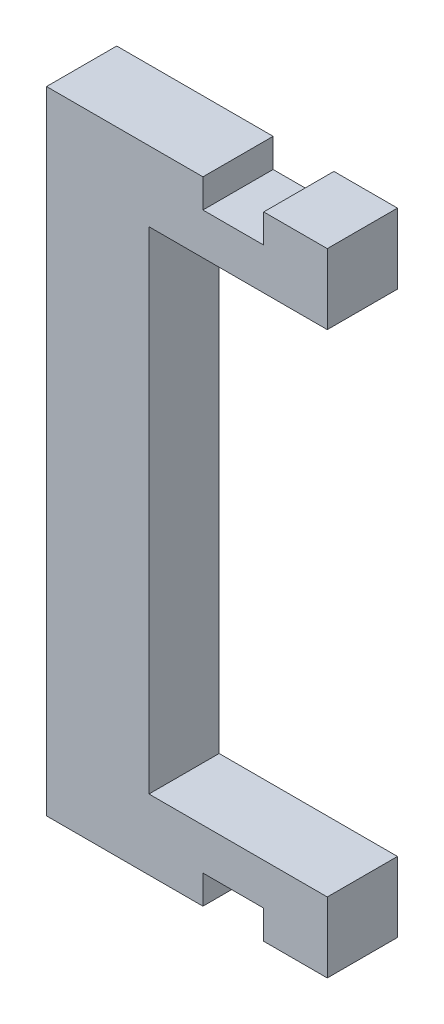
SolidWorks part; units mm, degrees
material "Polyurethane Foam Rigid"
ref_plane "Front Plane" through (0, 0, 0) normal (1, 0, 0) x (0, 1, 0)
ref_plane "Top Plane" through (0, 0, 0) normal (0, 0, 1) x (0, 1, 0)
ref_plane "Right Plane" through (0, 0, 0) normal (0, 1, 0) x (-1, 0, 0)
sketch "Sketch1" plane through (0, 0, 0) normal (0, 0, 1) x (0, 1, 0)
  line L0 (114.3, 0) -> (114.3, 64.5305) construction
  line L1 (0, 0) -> (228.6, 0)
  line L2 (0, 0) -> (0, 101.6)
  line L3 (0, 101.6) -> (228.6, 101.6)
  line L4 (228.6, 0) -> (228.6, 101.6)
  line L5 (25.4, 0) -> (203.2, 0)
  line L6 (25.4, 0) -> (25.4, 64.5305)
  line L7 (25.4, 64.5305) -> (203.2, 64.5305)
  line L8 (203.2, 0) -> (203.2, 64.5305)
  line L9 (0, 23) -> (10.4, 23)
  line L10 (0, 23) -> (0, 45)
  line L11 (0, 45) -> (10.4, 45)
  line L12 (10.4, 23) -> (10.4, 45)
  line L13 (228.6, 23) -> (218.2, 23)
  line L14 (218.2, 23) -> (218.2, 45)
  line L15 (228.6, 45) -> (218.2, 45)
  dimension "D1" = 228.6
  dimension "D2" = 101.6
  dimension "D3" = 25.4
  dimension "D4" = 64.5305
  dimension "D5" = 25.4
  dimension "D6" = 23
  dimension "D7" = 15
  dimension "D8" = 22
extrude "Boss-Extrude1" add sketch "Sketch1" along normal blind 25.4 contours L8 L1 L4 L3 L2 L6 L7
